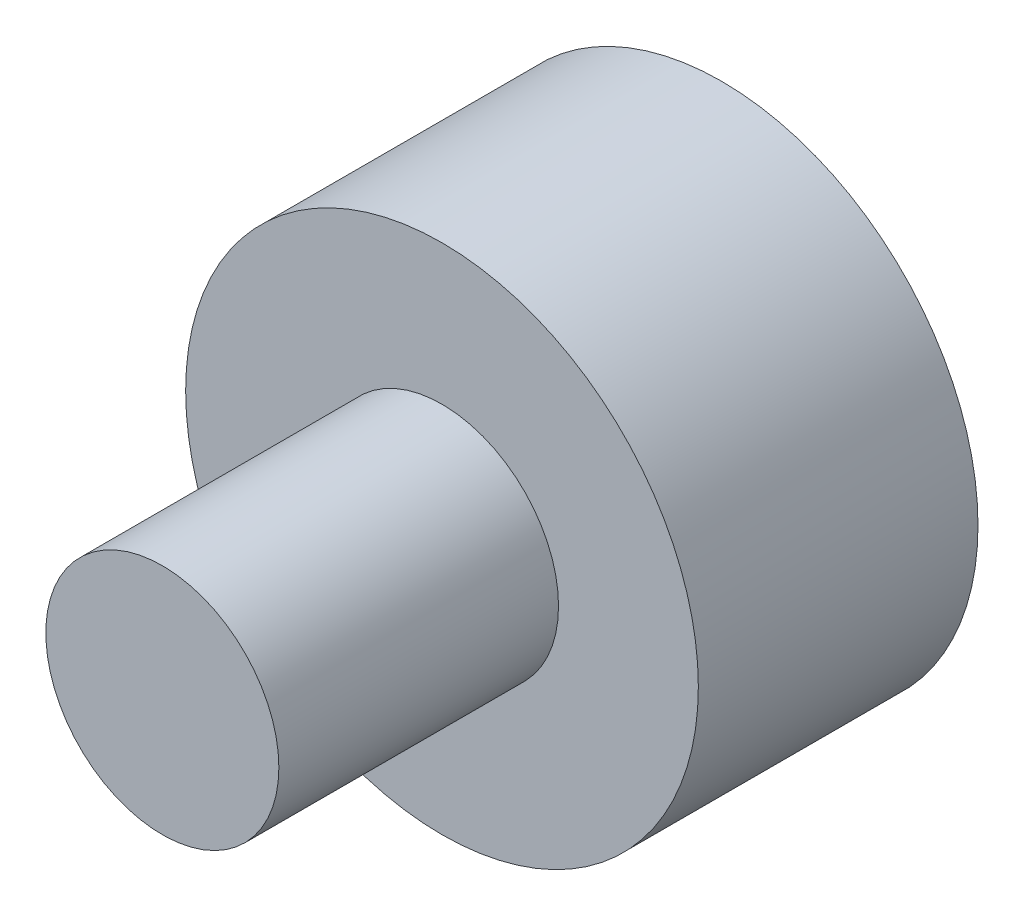
SolidWorks part; units mm, degrees
ref_plane "前视基准面" through (0, 0, 0) normal (0, 0, 1) x (1, 0, 0)
ref_plane "上视基准面" through (0, 0, 0) normal (0, 1, 0) x (1, 0, 0)
ref_plane "右视基准面" through (0, 0, 0) normal (1, 0, 0) x (0, 0, -1)
other "Configuration Table"
sketch "草图1" plane through (0, 0, 0) normal (0, 0, 1) x (1, 0, 0)
  circle A0 centre (0, 0) radius 2.75
  dimension "D1" = 5.5
extrude "凸台-拉伸1" add sketch "草图1" along normal blind 3
sketch "草图2" plane through (0, 0, 3) normal (0, 0, 1) x (1, 0, 0)
  circle A0 centre (0, 0) radius 1.25
  dimension "D1" = 2.5
extrude "凸台-拉伸2" add sketch "草图2" along normal blind 3
